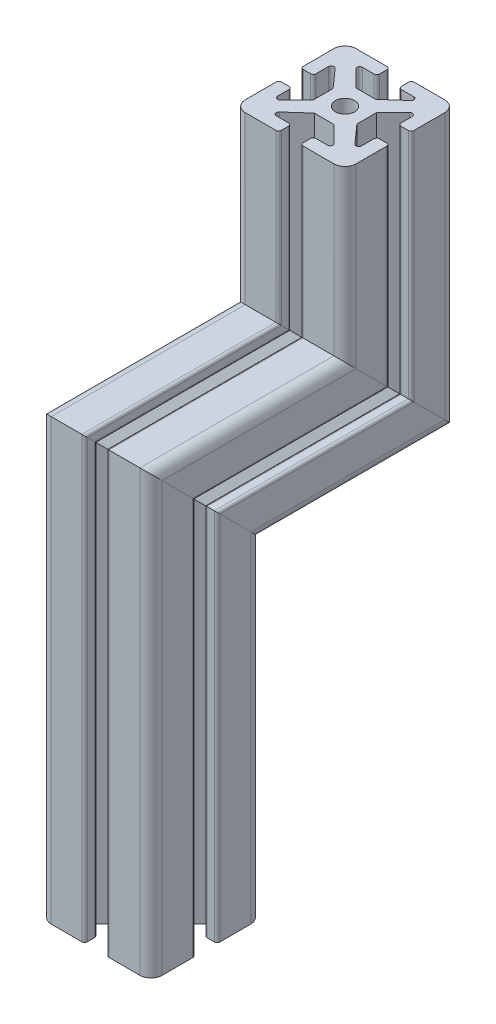
SolidWorks part; units mm, degrees
ref_plane "Front Plane" through (0, 0, 0) normal (0, 0, 1) x (1, 0, 0)
ref_plane "Top Plane" through (0, 0, 0) normal (0, 1, 0) x (1, 0, 0)
ref_plane "Right Plane" through (0, 0, 0) normal (1, 0, 0) x (0, 0, -1)
sketch "Sketch2" plane through (0, 0, 0) normal (1, 0, 0) x (0, 0, -1)
  line L0 (0, 0) -> (0, -80)
  line L1 (0, -80) -> (-70, -80)
  line L2 (-70, -80) -> (-70, -218.6)
  dimension "D1" = 80
  dimension "D2" = 70
  dimension "D3" = 138.6
other "001 40-40_EXTRUSION(1)"
ref_plane "Plane1" through (0, 0, 0) normal (0, -1, 0) x (0, 0, -1)
sketch "Sketch1" plane through (0, 0, 0) normal (0, -1, 0) x (0, 0, -1)
  line L0 (-20, 20) -> (20, -20) construction
  line L1 (-20, -20) -> (20, -20) construction
  line L2 (-20, -20) -> (-20, 20) construction
  line L3 (-20, 20) -> (20, 20) construction
  line L4 (20, -20) -> (20, 20) construction
  line L5 (-20, -20) -> (20, 20) construction
  line L6 (-0.5117, 7.6847) -> (3.7499, 7.6847)
  line L7 (3.7499, 7.6847) -> (9.6997, 13.625)
  line L8 (8.9931, 15.3327) -> (4.8456, 15.3327)
  line L9 (3.8456, 16.3327) -> (3.8456, 19)
  line L10 (4.8456, 20) -> (16, 20)
  line L11 (20, 16) -> (20, 4.9611)
  line L12 (19, 3.9611) -> (16.3883, 3.9611)
  line L13 (15.3883, 4.9611) -> (15.3883, 9.4086)
  line L14 (13.6417, 10.0739) -> (7.6847, 3.3888)
  line L15 (7.6847, 3.3888) -> (7.6847, 0.5117)
  line L16 (7.6847, -3.7499) -> (13.625, -9.6997)
  line L17 (10.0739, -13.6417) -> (3.3888, -7.6847)
  line L18 (7.6847, 0.5117) -> (7.6847, -3.7499)
  line L19 (15.3327, -8.9931) -> (15.3327, -4.8456)
  line L20 (16.3327, -3.8456) -> (19, -3.8456)
  line L21 (20, -4.8456) -> (20, -16)
  line L22 (16, -20) -> (4.9611, -20)
  line L23 (3.9611, -19) -> (3.9611, -16.3883)
  line L24 (4.9611, -15.3883) -> (9.4086, -15.3883)
  line L25 (3.3888, -7.6847) -> (0.5117, -7.6847)
  line L26 (-3.7499, -7.6847) -> (-9.6997, -13.625)
  line L27 (-13.6417, -10.0739) -> (-7.6847, -3.3888)
  line L28 (0.5117, -7.6847) -> (-3.7499, -7.6847)
  line L29 (-8.9931, -15.3327) -> (-4.8456, -15.3327)
  line L30 (-3.8456, -16.3327) -> (-3.8456, -19)
  line L31 (-4.8456, -20) -> (-16, -20)
  line L32 (-20, -16) -> (-20, -4.9611)
  line L33 (-19, -3.9611) -> (-16.3883, -3.9611)
  line L34 (-15.3883, -4.9611) -> (-15.3883, -9.4086)
  line L35 (-7.6847, -3.3888) -> (-7.6847, -0.5117)
  line L36 (-7.6847, 3.7499) -> (-13.625, 9.6997)
  line L37 (-10.0739, 13.6417) -> (-3.3888, 7.6847)
  line L38 (-7.6847, -0.5117) -> (-7.6847, 3.7499)
  line L39 (-15.3327, 8.9931) -> (-15.3327, 4.8456)
  line L40 (-16.3327, 3.8456) -> (-19, 3.8456)
  line L41 (-20, 4.8456) -> (-20, 16)
  line L42 (-16, 20) -> (-4.9611, 20)
  line L43 (-3.9611, 19) -> (-3.9611, 16.3883)
  line L44 (-4.9611, 15.3883) -> (-9.4086, 15.3883)
  line L45 (-3.3888, 7.6847) -> (-0.5117, 7.6847)
  circle A0 centre (0, 0) radius 3.4925
  arc A1 (20, 4.9611) -> (19, 3.9611) centre (19, 4.9611) cw
  arc A2 (16.3883, 3.9611) -> (15.3883, 4.9611) centre (16.3883, 4.9611) cw
  arc A3 (4.8456, 15.3327) -> (3.8456, 16.3327) centre (4.8456, 16.3327) cw
  arc A4 (3.8456, 19) -> (4.8456, 20) centre (4.8456, 19) cw
  arc A5 (9.6997, 13.625) -> (8.9931, 15.3327) centre (8.9931, 14.3327) ccw
  arc A6 (15.3883, 9.4086) -> (13.6417, 10.0739) centre (14.3883, 9.4086) ccw
  arc A7 (20, 16) -> (16, 20) centre (16, 16) ccw
  arc A8 (15.3327, -4.8456) -> (16.3327, -3.8456) centre (16.3327, -4.8456) cw
  arc A9 (19, -3.8456) -> (20, -4.8456) centre (19, -4.8456) cw
  arc A10 (16, -20) -> (20, -16) centre (16, -16) ccw
  arc A11 (4.9611, -20) -> (3.9611, -19) centre (4.9611, -19) cw
  arc A12 (3.9611, -16.3883) -> (4.9611, -15.3883) centre (4.9611, -16.3883) cw
  arc A13 (9.4086, -15.3883) -> (10.0739, -13.6417) centre (9.4086, -14.3883) ccw
  arc A14 (13.625, -9.6997) -> (15.3327, -8.9931) centre (14.3327, -8.9931) ccw
  arc A15 (-4.8456, -15.3327) -> (-3.8456, -16.3327) centre (-4.8456, -16.3327) cw
  arc A16 (-3.8456, -19) -> (-4.8456, -20) centre (-4.8456, -19) cw
  arc A17 (-20, -16) -> (-16, -20) centre (-16, -16) ccw
  arc A18 (-20, -4.9611) -> (-19, -3.9611) centre (-19, -4.9611) cw
  arc A19 (-16.3883, -3.9611) -> (-15.3883, -4.9611) centre (-16.3883, -4.9611) cw
  arc A20 (-15.3883, -9.4086) -> (-13.6417, -10.0739) centre (-14.3883, -9.4086) ccw
  arc A21 (-9.6997, -13.625) -> (-8.9931, -15.3327) centre (-8.9931, -14.3327) ccw
  arc A22 (-15.3327, 4.8456) -> (-16.3327, 3.8456) centre (-16.3327, 4.8456) cw
  arc A23 (-19, 3.8456) -> (-20, 4.8456) centre (-19, 4.8456) cw
  arc A24 (-16, 20) -> (-20, 16) centre (-16, 16) ccw
  arc A25 (-4.9611, 20) -> (-3.9611, 19) centre (-4.9611, 19) cw
  arc A26 (-3.9611, 16.3883) -> (-4.9611, 15.3883) centre (-4.9611, 16.3883) cw
  arc A27 (-9.4086, 15.3883) -> (-10.0739, 13.6417) centre (-9.4086, 14.3883) ccw
  arc A28 (-13.625, 9.6997) -> (-15.3327, 8.9931) centre (-14.3327, 8.9931) ccw
  point P103 (0, 0)
  dimension "D3" = 1
  dimension "D4" = 4
  dimension "D1" = 40
  dimension "D2" = 40
